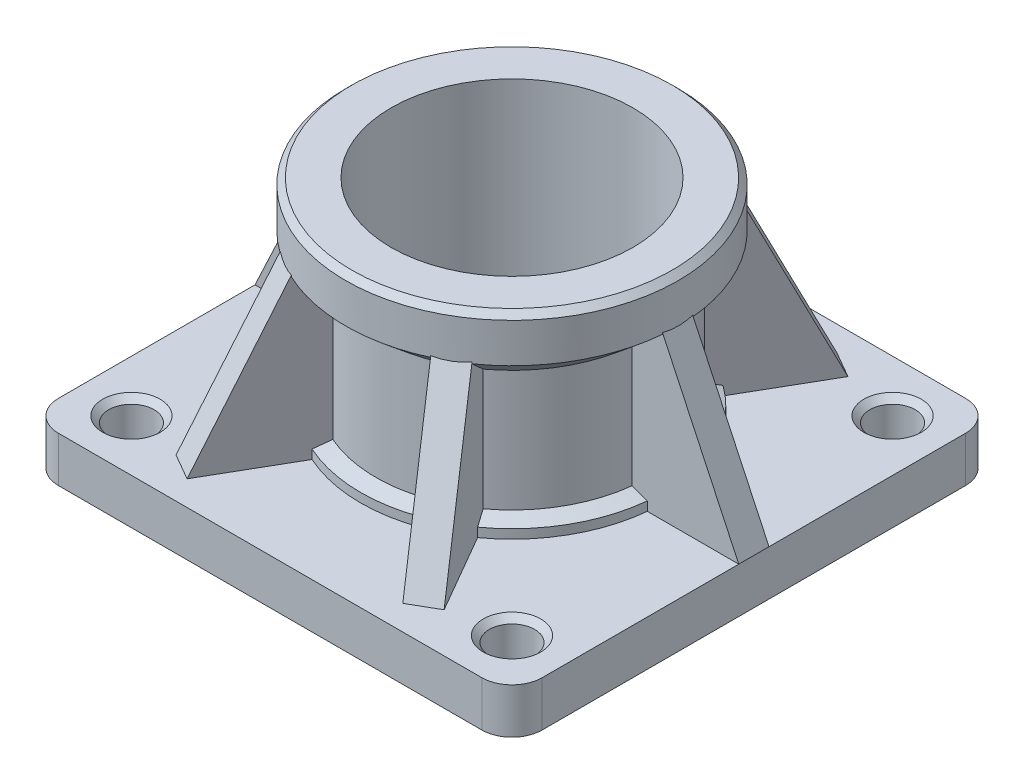
SolidWorks part; units mm, degrees
ref_plane "Front Plane" through (0, 0, 0) normal (0, 0, 1) x (1, 0, 0)
ref_plane "Top Plane" through (0, 0, 0) normal (0, 1, 0) x (1, 0, 0)
ref_plane "Right Plane" through (0, 0, 0) normal (1, 0, 0) x (0, 0, -1)
sketch "Base Sketch" plane through (0, 0, 0) normal (0, 1, 0) x (1, 0, 0)
  line L1 (101.6, -101.6) -> (-101.6, -101.6)
  line L2 (101.6, -101.6) -> (101.6, 101.6)
  line L3 (101.6, 101.6) -> (-101.6, 101.6)
  line L4 (-101.6, -101.6) -> (-101.6, 101.6)
  line L5 (101.6, -101.6) -> (-101.6, 101.6) construction
  line L6 (101.6, 101.6) -> (-101.6, -101.6) construction
  point P0 (0, 0)
  dimension "Width" = 203.2
extrude "Base Feature" add sketch "Base Sketch" along normal blind 19.05
sketch "Shaft Housing Sketch" plane through (0, 0, 0) normal (0, 0, 1) x (1, 0, 0)
  line L0 (63.5, 19.05) -> (63.5, 22.86)
  line L1 (-101.6, 19.05) -> (101.6, 19.05) construction
  line L2 (63.5, 22.86) -> (57.15, 25.1712)
  line L3 (57.15, 25.1712) -> (57.15, 75.9712)
  line L4 (57.15, 75.9712) -> (69.85, 86.6278)
  line L5 (69.85, 86.6278) -> (69.85, 105.6778)
  line L6 (69.85, 105.6778) -> (50.8, 105.6778)
  line L7 (50.8, 105.6778) -> (50.8, 19.05)
  line L8 (50.8, 19.05) -> (63.5, 19.05)
  line L9 (0, 0) -> (0, -38.1783) construction
  dimension "ID" = 50.8
  dimension "D2" = 12.7
  dimension "D3" = 3.81
  dimension "D4" = 110
  dimension "D5" = 50.8
  dimension "D6" = 130
  dimension "D7" = 6.35
  dimension "D8" = 19.05
  dimension "D9" = 19.05
revolve "Shaft Housing Feature" add sketch "Shaft Housing Sketch" angle 360 about L9
sketch "Shaft Hole Sketch" plane through (0, 105.6778, 0) normal (0, 1, 0) x (1, 0, 0)
  circle A0 centre (0, 0) radius 50.8 construction
  circle A1 centre (0, 0) radius 50.8
extrude "Shaft Hole Feature" cut sketch "Shaft Hole Sketch" against normal through all
fillet "Base Fillet" radius 12.7 4 edges at (-101.6, 9.525, -101.6) (101.6, 9.525, -101.6) (101.6, 9.525, 101.6) (-101.6, 9.525, 101.6)
sketch "Bolting Holes Sketch" plane through (0, 19.05, 0) normal (0, 1, 0) x (1, 0, 0)
  line L0 (-97.8803, 97.8803) -> (97.8803, -97.8803) construction
  line L1 (-97.8803, -97.8803) -> (97.8803, 97.8803) construction
  circle A0 centre (-79.9197, 79.9197) radius 9.525
  arc A1 (-88.9, 101.6) -> (-101.6, 88.9) centre (-88.9, 88.9) ccw construction
  arc A2 (88.9, -101.6) -> (101.6, -88.9) centre (88.9, -88.9) ccw construction
  arc A3 (-101.6, -88.9) -> (-88.9, -101.6) centre (-88.9, -88.9) ccw construction
  arc A4 (101.6, 88.9) -> (88.9, 101.6) centre (88.9, 88.9) ccw construction
  circle A5 centre (79.9197, 79.9197) radius 9.525
  circle A6 centre (79.9197, -79.9197) radius 9.525
  circle A7 centre (-79.9197, -79.9197) radius 9.525
  dimension "D1" = 19.05
  dimension "D3" = 25.4
  dimension "D4" = 25.4
  dimension "D2" = 25.4
  dimension "D5" = 25.4
extrude "Bolting Holes Feature" cut sketch "Bolting Holes Sketch" against normal through all
sketch "Rib Support Sketch" plane through (0, 0, 0) normal (0, 0, 1) x (1, 0, 0)
  line L0 (-69.85, 86.6278) -> (-101.6, 19.05)
  line L1 (69.85, 86.6278) -> (-69.85, 86.6278) construction
rib "Rib Support Feature" sketch "Rib Support Sketch" sketch "Rib Support Sketch" thickness 12.7 extrusion direction parallel to sketch draft on no parameters "D1"=12.7
pattern_circular "Rib Support Pattern" count 6 over 360 about axis through (0, 0, 0) along (0, 1, 0) of "Rib Support Feature"
fillet "Shaft Housing Fillet" [suppressed] radius 7.62
chamfer "Chamfer1" distance 2.54 angle 45 5 edges at (0, 105.6778, 69.85) (79.9197, 19.05, 89.4447) (79.9197, 19.05, -70.3947) (-79.9197, 19.05, 89.4447) (-79.9197, 19.05, -70.3947)
